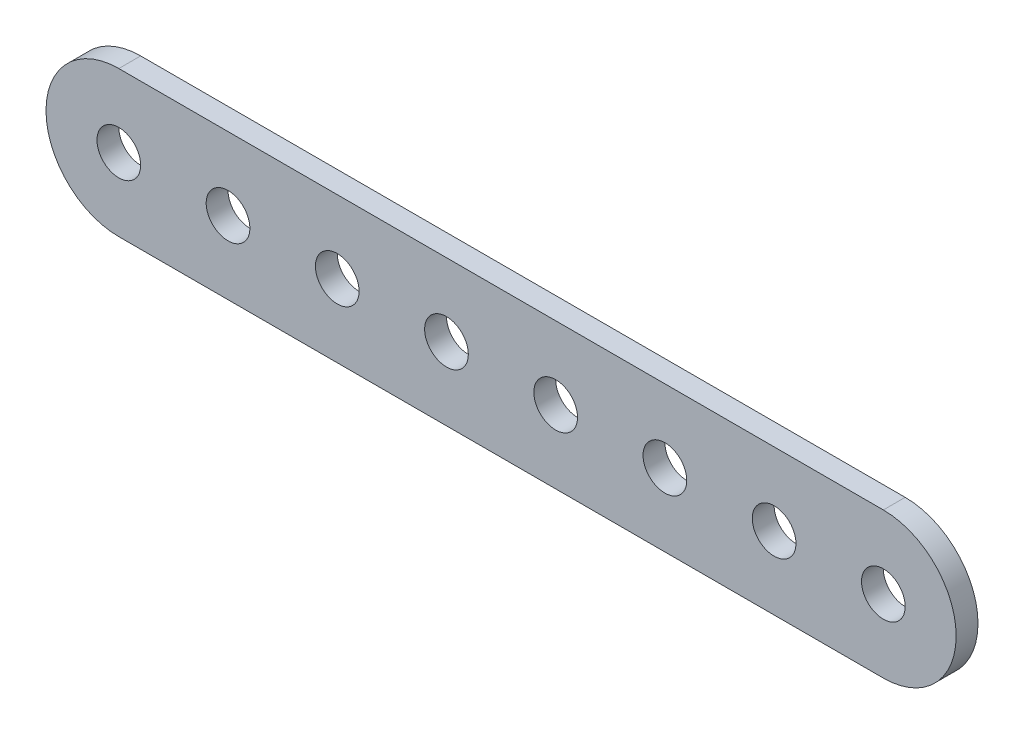
SolidWorks part; units mm, degrees
ref_plane "Front Plane" through (0, 0, 0) normal (0, 0, 1) x (1, 0, 0)
ref_plane "Top Plane" through (0, 0, 0) normal (0, 1, 0) x (1, 0, 0)
ref_plane "Right Plane" through (0, 0, 0) normal (1, 0, 0) x (0, 0, -1)
sketch "Sketch3" plane through (0, 0, 0) normal (0, 0, 1) x (1, 0, 0)
  line L0 (52.5, 0) -> (-52.5, 0) construction
  line L1 (-52.5, 10) -> (52.5, 10)
  line L2 (52.5, -10) -> (-52.5, -10)
  line L3 (0, 21.2343) -> (0, 0) construction
  circle A0 centre (52.5, 0) radius 3
  circle A1 centre (-52.5, 0) radius 3
  arc A2 (-52.5, 10) -> (-52.5, -10) centre (-52.5, 0) ccw
  circle A3 centre (-37.5, 0) radius 3
  circle A4 centre (-22.5, 0) radius 3
  circle A5 centre (-7.5, 0) radius 3
  circle A6 centre (7.5, 0) radius 3
  circle A7 centre (22.5, 0) radius 3
  circle A8 centre (37.5, 0) radius 3
  arc A9 (52.5, 10) -> (52.5, -10) centre (52.5, 0) cw
  point P25 (-57.5845, -10)
  dimension "D1" = 6
  dimension "D5" = 15
  dimension "D3" = 15
  dimension "D4" = 20
  dimension "D2" = 4
extrude "Boss-Extrude1" add sketch "Sketch3" along normal blind 3
